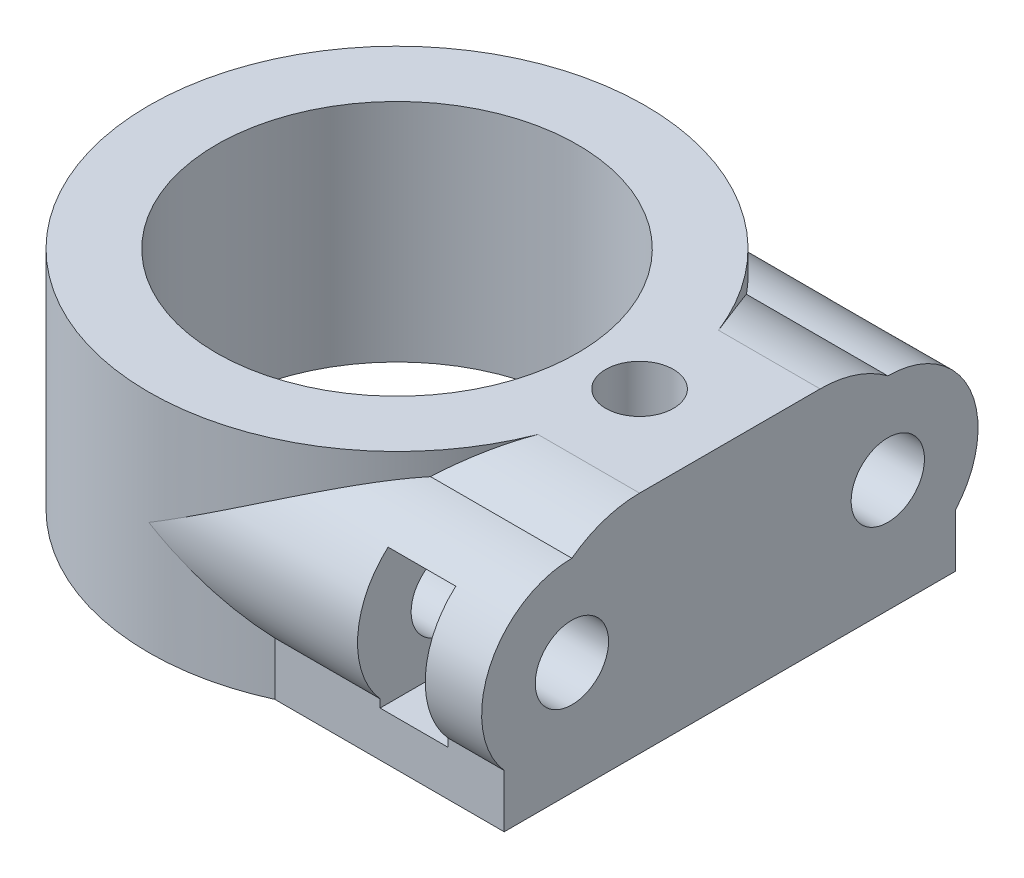
SolidWorks part; units mm, degrees
material "ABS"
ref_plane "Front Plane" through (0, 0, 0) normal (0, 0, 1) x (1, 0, 0)
ref_plane "Top Plane" through (0, 0, 0) normal (0, 1, 0) x (1, 0, 0)
ref_plane "Right Plane" through (0, 0, 0) normal (1, 0, 0) x (0, 0, -1)
sketch "Sketch2" plane through (0, 0, 0) normal (0, 1, 0) x (1, 0, 0)
  circle A0 centre (0, 0) radius 11
  circle A1 centre (0, 0) radius 8
extrude "Boss-Extrude1" add sketch "Sketch2" along normal blind 10
ref_plane "Plane1" through (14.75, 0, 0) normal (1, 0, 0) x (0, 0, -1)
sketch "Sketch4" plane through (14.75, 0, 0) normal (1, 0, 0) x (0, 0, -1)
  line L1 (4, 10) -> (-4, 10)
  line L2 (10, 0) -> (-10, 0)
  line L3 (-10, 0) -> (-10, 2.3542)
  line L4 (0, 0) -> (0, 10) construction
  line L5 (11, 10) -> (-11, 10) construction
  line L6 (10, 0) -> (10, 2.3542)
  line L9 (0, 0) -> (0, 5) construction
  arc A1 (-7, 9) -> (-10, 2.3542) centre (-7, 5) ccw
  arc A2 (-4, 10) -> (-7, 9) centre (-4, 5) ccw
  arc A4 (7, 9) -> (10, 2.3542) centre (7, 5) cw
  arc A5 (4, 10) -> (7, 9) centre (4, 5) cw
  point P17 (-4, 5)
  dimension "D1" = 5
  dimension "D4" = 8
  dimension "D5" = 4
  dimension "D7" = 10
  dimension "D2" = 7
  dimension "D3" = 10
extrude "Boss-Extrude2" add sketch "Sketch4" against normal up to surface (10.1674 mm away)
sketch "Sketch6" plane through (0, 10, 0) normal (0, 1, 0) x (1, 0, 0)
  circle A0 centre (10.75, 0) radius 1.5
  dimension "D1" = 3
  dimension "D2" = 10.75
extrude "Cut-Extrude1" cut sketch "Sketch6" against normal through all
ref_plane "Plane2" through (12.25, 0, 0) normal (1, 0, 0) x (0, 0, -1)
sketch "Sketch11" plane through (12.25, 0, 0) normal (1, 0, 0) x (0, 0, -1)
  line L0 (10, 2.3542) -> (10, 2)
  line L1 (0, 0) -> (0, 10.6068) construction
  line L2 (-3.5359, 5) -> (-5.2679, 2)
  line L3 (9.6458, 8) -> (5.2679, 8)
  line L4 (5.2679, 8) -> (3.5359, 5)
  line L5 (3.5359, 5) -> (5.2679, 2)
  line L6 (5.2679, 2) -> (10, 2)
  line L7 (-5.2679, 2) -> (-10, 2)
  line L8 (-10, 2.3542) -> (-10, 2)
  line L9 (9.5981, 3.5) -> (10.4641, 5) [skipped]
  line L10 (9.5981, 6.5) -> (8.7321, 8) [skipped]
  line L11 (-9.6458, 8) -> (-5.2679, 8)
  line L12 (-5.2679, 8) -> (-3.5359, 5)
  circle A0 centre (7, 5) radius 3 construction
  arc A2 (10, 2.3542) -> (7, 9) centre (7, 5) ccw construction
  arc A3 (10, 2.3542) -> (9.6458, 8) centre (7, 5) ccw
  arc A4 (-10, 2.3542) -> (-9.6458, 8) centre (-7, 5) cw
  dimension "D1" = 6
extrude "Cut-Extrude2" cut sketch "Sketch11" against normal blind 3
sketch "Sketch13" plane through (14.75, 0, 0) normal (1, 0, 0) x (0, 0, -1)
  line L0 (0, 0) -> (0, 7.5476) construction
  line L1 (-10, 0) -> (10, 0) construction
  circle A0 centre (-7, 5) radius 1.625
  circle A1 centre (7, 5) radius 1.625
  dimension "D1" = 5
  dimension "D3" = 3.25
  dimension "D2" = 7
extrude "Cut-Extrude3" cut sketch "Sketch13" against normal blind 10
